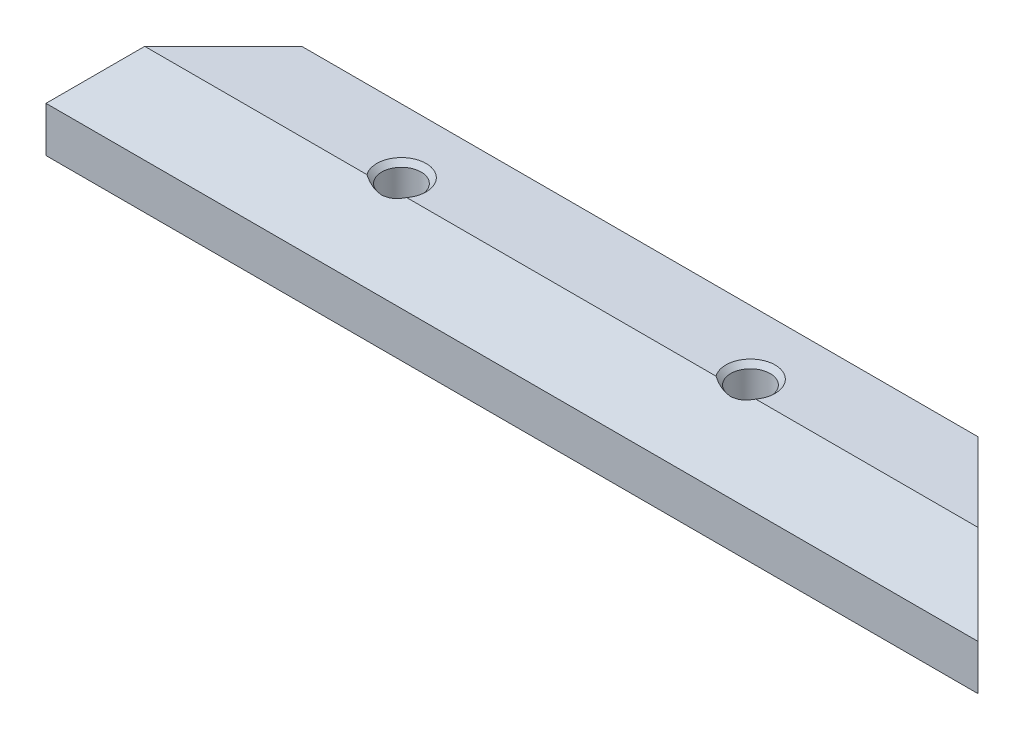
SolidWorks part; units mm, degrees
ref_plane "Front Plane" through (0, 0, 0) normal (0, 0, 1) x (1, 0, 0)
ref_plane "Top Plane" through (0, 0, 0) normal (0, 1, 0) x (1, 0, 0)
ref_plane "Right Plane" through (0, 0, 0) normal (1, 0, 0) x (0, 0, -1)
sketch "Sketch1" plane through (0, 0, 0) normal (0, 1, 0) x (1, 0, 0)
  line L0 (-94.41, 0) -> (94.41, 0)
  line L1 (-68.5, 25.91) -> (68.5, 25.91)
  line L2 (-94.41, 0) -> (-68.5, 25.91)
  line L3 (68.5, 25.91) -> (94.41, 0)
  point P4 (0, 0)
  point P8 (0, 25.91)
  dimension "D1" = 137
  dimension "D2" = 45
  dimension "D3" = 45
  dimension "D4" = 25.91
extrude "Boss-Extrude1" add sketch "Sketch1" along normal blind 3
sketch "Sketch4" plane through (0, 3, 0) normal (0, 1, 0) x (1, 0, 0)
  line L0 (0, -1000) -> (0, 49000) construction
  line L1 (-94.41, 0) -> (94.41, 0) construction
  circle A0 centre (0, 133.2) radius 120 construction
  point P3 (87.8588, 122.1848)
  point P7 (0, 0)
  dimension "D2" = 240
  dimension "D1" = 133.2
sketch "Sketch5" plane through (0, 3, 0) normal (0, 1, 0) x (1, 0, 0)
  line L0 (68.5, 25.91) -> (-68.5, 25.91) construction
  line L1 (-64.4969, 25.91) -> (-68.5, 25.91)
  line L2 (-68.5, 25.91) -> (-94.41, 0)
  line L3 (-94.41, 0) -> (94.41, 0)
  line L4 (94.41, 0) -> (68.5, 25.91)
  line L5 (68.5, 25.91) -> (64.4969, 25.91)
  arc A0 (-45.5273, 22.1718) -> (45.5273, 22.1718) centre (0, 133.2) ccw
  circle A1 centre (0, 133.2) radius 120 construction
  arc A2 (45.5273, 22.1718) -> (64.4969, 25.91) centre (64.4969, -24.09) cw
  arc A3 (-45.5273, 22.1718) -> (-64.4969, 25.91) centre (-64.4969, -24.09) ccw
  point P18 (53.7481, 25.91)
  point P21 (-53.7481, 25.91)
  dimension "D1" = 50
extrude "Boss-Extrude2" add sketch "Sketch5" along normal blind 12
sketch "Sketch7" plane through (0, 15, 0) normal (0, 1, 0) x (1, 0, 0)
  line L0 (-94.41, 0) -> (-68.5, 25.91)
  line L1 (-68.5, 25.91) -> (68.5, 25.91)
  line L2 (68.5, 25.91) -> (94.41, 0)
  line L3 (94.41, 0) -> (-94.41, 0)
  point P8 (69.5, 26.31)
extrude "Boss-Extrude3" add sketch "Sketch7" along normal blind 4.17
sketch "Sketch3" plane through (0, 3, 0) normal (0, 1, 0) x (1, 0, 0)
  line L0 (0, -1000) -> (0, 49000) construction
  line L1 (-988.1148, 12.955) -> (49011.8852, 12.955) construction
  line L2 (-68.5, 25.91) -> (-94.41, 0) construction
  line L3 (-35.3553, 12.955) -> (0, -22.4003) construction
  line L4 (0, -22.4003) -> (35.3553, 12.955) construction
  circle A0 centre (-35.3553, 12.955) radius 2
  circle A1 centre (35.3553, 12.955) radius 2
  point P11 (-81.455, 12.955)
  point P14 (0, -22.4003)
  dimension "D1" = 4
  dimension "D2" = 4
  dimension "D3" = 50
  dimension "D4" = 50
  dimension "D5" = 90
extrude "Cut-Extrude1" cut sketch "Sketch3" against normal through all both and the other way through all
chamfer "Chamfer1" distance 10 angle 45 1 edges at (0, 19.17, 0)
sketch "Sketch8" plane through (0, 19.17, 0) normal (0, 1, 0) x (1, 0, 0)
  circle A0 centre (-35.3553, 12.955) radius 4
  circle A1 centre (35.3553, 12.955) radius 4
  dimension "D1" = 8
  dimension "D2" = 8
extrude "Cut-Extrude2" cut sketch "Sketch8" against normal offset from surface (16.17 mm away) 3 up to face at (-35.3553, 0, -10.955)
chamfer "Chamfer2" distance 1 angle 45 2 edges at (-35.3553, 19.17, -16.955) (35.3553, 19.17, -16.955)
